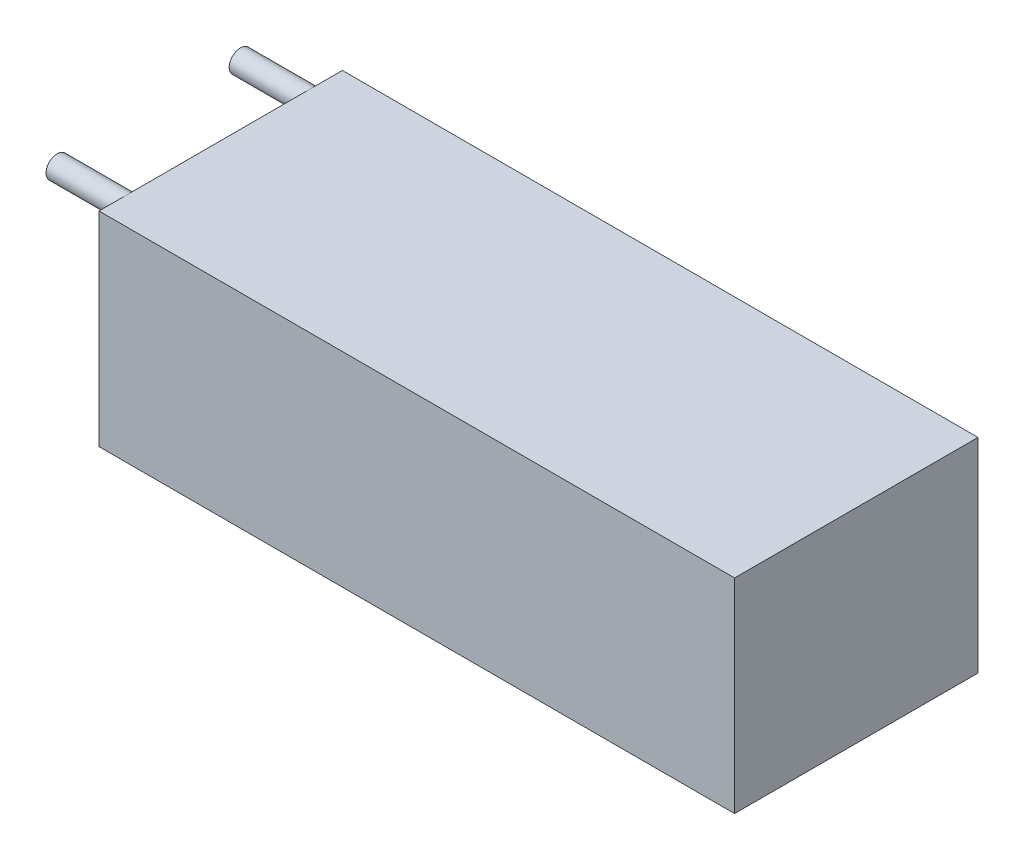
SolidWorks part; units mm, degrees
ref_plane "前视基准面" through (0, 0, 0) normal (0, 0, 1) x (1, 0, 0)
ref_plane "上视基准面" through (0, 0, 0) normal (0, 1, 0) x (1, 0, 0)
ref_plane "右视基准面" through (0, 0, 0) normal (1, 0, 0) x (0, 0, -1)
sketch "草图1" plane through (0, 0, 0) normal (0, 1, 0) x (1, 0, 0)
  line L1 (0, 0) -> (135, 0)
  line L2 (0, 0) -> (0, 51.7)
  line L3 (0, 51.7) -> (135, 51.7)
  line L4 (135, 0) -> (135, 51.7)
  dimension "D1" = 135
  dimension "D2" = 51.7
extrude "凸台-拉伸1" add sketch "草图1" along normal blind 43.34
sketch "草图2" plane through (0, 0, 0) normal (-1, 0, 0) x (0, 0, 1)
  line L0 (-33.2488, 1.9727) -> (-30.2488, 1.9727) construction
  circle A0 centre (-33.2488, 1.9727) radius 1.0863
  circle A1 centre (-45.0376, 40.9398) radius 2.3728
  circle A2 centre (-6.1198, 40.9398) radius 2.362
  circle A3 centre (-30.2488, 1.9727) radius 1.0863
  circle A4 centre (-27.2488, 1.9727) radius 1.0863
  circle A5 centre (-24.2488, 1.9727) radius 1.0863
  circle A6 centre (-21.2488, 1.9727) radius 1.0863
  circle A7 centre (-18.2488, 1.9727) radius 1.0863
  dimension "D1" = 3
  dimension "D2" = 6
extrude "凸台-拉伸2" add sketch "草图2" along normal blind 15 contours A0
